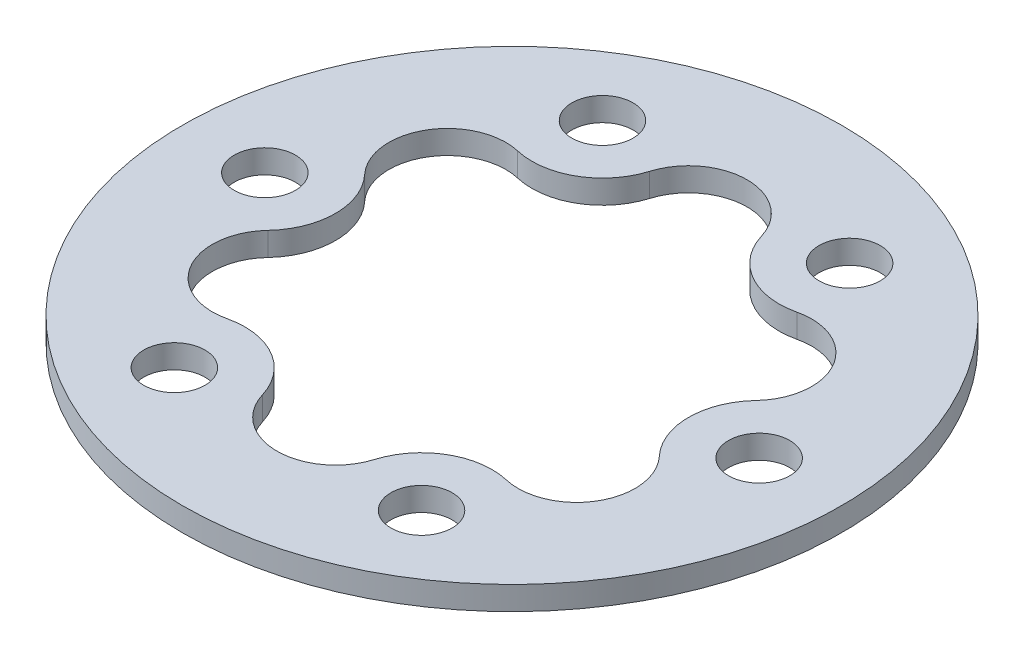
SolidWorks part; units mm, degrees
material "ABS"
ref_plane "前视基准面" through (0, 0, 0) normal (0, 0, 1) x (1, 0, 0)
ref_plane "上视基准面" through (0, 0, 0) normal (0, 1, 0) x (1, 0, 0)
ref_plane "右视基准面" through (0, 0, 0) normal (1, 0, 0) x (0, 0, -1)
sketch "草图1" plane through (0, 0, 0) normal (0, 1, 0) x (1, 0, 0)
  line L0 (0, 25) -> (0, 0) construction
  line L1 (0, 0) -> (10.5, 18.1865) construction
  circle A0 centre (0, 0) radius 28
  circle A1 centre (0, 0) radius 25 construction
  circle A2 centre (0, 25) radius 1.25 construction
  circle A3 centre (21.6506, 12.5) radius 1.25 construction
  circle A4 centre (21.6506, -12.5) radius 1.25 construction
  circle A5 centre (0, -25) radius 1.25 construction
  circle A6 centre (-21.6506, -12.5) radius 1.25 construction
  circle A7 centre (-21.6506, 12.5) radius 1.25 construction
  circle A8 centre (0, 0) radius 15 construction
  circle A9 centre (0, 15) radius 4 construction
  circle A10 centre (12.9904, -7.5) radius 4 construction
  circle A11 centre (-12.9904, -7.5) radius 4 construction
  circle A12 centre (0, 0) radius 21 construction
  circle A13 centre (10.5, 18.1865) radius 2.6
  circle A14 centre (21, 0) radius 2.6
  circle A15 centre (10.5, -18.1865) radius 2.6
  circle A16 centre (-10.5, -18.1865) radius 2.6
  circle A17 centre (-21, 0) radius 2.6
  circle A18 centre (-10.5, 18.1865) radius 2.6
  dimension "D1" = 2.5
  dimension "D2" = 50
  dimension "D3" = 56
  dimension "D5" = 30
  dimension "D6" = 8
  dimension "D9" = 5.2
  dimension "D10" = 42
  dimension "D8" = 30
  dimension "D4" = 6
  dimension "D7" = 3
  dimension "D11" = 6
extrude "凸台-拉伸1" add sketch "草图1" along normal blind 2
sketch "草图4" plane through (0, 2, 0) normal (0, 1, 0) x (1, 0, 0)
  circle A0 centre (0, 0) radius 15 construction
  circle A1 centre (0, 15) radius 4 construction
  circle A2 centre (12.9904, 7.5) radius 4 construction
  circle A3 centre (12.9904, -7.5) radius 4 construction
  circle A4 centre (0, -15) radius 4 construction
  circle A5 centre (-12.9904, -7.5) radius 4 construction
  circle A6 centre (-12.9904, 7.5) radius 4 construction
  arc A7 (4.7586, 16.4441) -> (11.8617, 12.3431) centre (10.5, 18.1865) ccw
  arc A8 (-4.7586, 16.4441) -> (4.7586, 16.4441) centre (0, 15) cw
  arc A9 (11.8617, 12.3431) -> (16.6203, 4.101) centre (12.9904, 7.5) cw
  arc A10 (16.6203, 4.101) -> (16.6203, -4.101) centre (21, 0) ccw
  arc A11 (16.6203, -4.101) -> (11.8617, -12.3431) centre (12.9904, -7.5) cw
  arc A12 (11.8617, -12.3431) -> (4.7586, -16.4441) centre (10.5, -18.1865) ccw
  arc A13 (4.7586, -16.4441) -> (-4.7586, -16.4441) centre (0, -15) cw
  arc A14 (-4.7586, -16.4441) -> (-11.8617, -12.3431) centre (-10.5, -18.1865) ccw
  arc A15 (-11.8617, -12.3431) -> (-16.6203, -4.101) centre (-12.9904, -7.5) cw
  arc A16 (-16.6203, -4.101) -> (-16.6203, 4.101) centre (-21, 0) ccw
  arc A17 (-16.6203, 4.101) -> (-11.8617, 12.3431) centre (-12.9904, 7.5) cw
  arc A18 (-11.8617, 12.3431) -> (-4.7586, 16.4441) centre (-10.5, 18.1865) ccw
  dimension "D1" = 30
  dimension "D2" = 8
  dimension "D4" = 6
  dimension "D3" = 6
  dimension "D5" = 6
extrude "切除-拉伸2" cut sketch "草图4" against normal through all and the other way through all
move or copy body "实体-移动/复制1" [suppressed] bodies to move or copy 109
